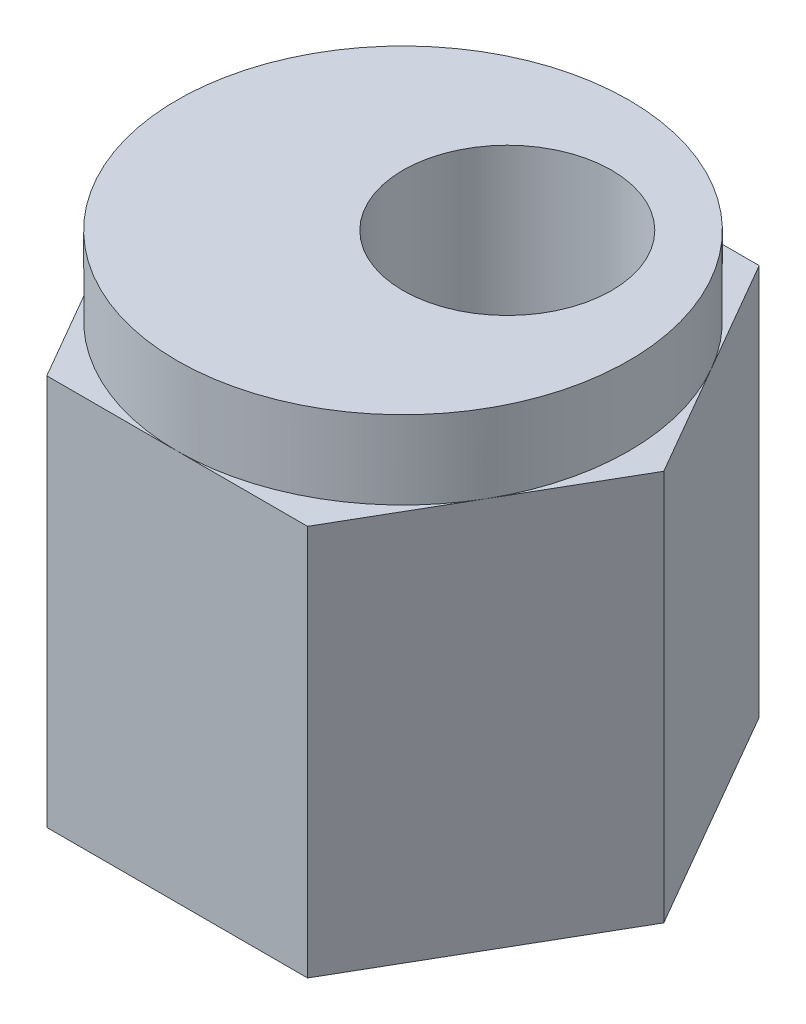
SolidWorks part; units mm, degrees
ref_plane "Front Plane" through (0, 0, 0) normal (0, 0, 1) x (1, 0, 0)
ref_plane "Top Plane" through (0, 0, 0) normal (0, 1, 0) x (1, 0, 0)
ref_plane "Right Plane" through (0, 0, 0) normal (1, 0, 0) x (0, 0, -1)
sketch "Sketch1" plane through (0, 0, 0) normal (0, 1, 0) x (1, 0, 0)
  line L1 (10, 0) -> (5, 8.6603)
  line L2 (5, 8.6603) -> (-5, 8.6603)
  line L3 (-5, 8.6603) -> (-10, 0)
  line L4 (-10, 0) -> (-5, -8.6603)
  line L5 (-5, -8.6603) -> (5, -8.6603)
  line L6 (5, -8.6603) -> (10, 0)
  circle A0 centre (0, 0) radius 8.6603 construction
  circle A1 centre (2, 2) radius 4
  dimension "D2" = 8
  dimension "D1" = 10
  dimension "D3" = 2
  dimension "D4" = 2
extrude "Boss-Extrude1" add sketch "Sketch1" along normal blind 18
sketch "Sketch3" plane through (0, 18, 0) normal (0, 1, 0) x (1, 0, 0)
  circle A0 centre (0, 0) radius 8.6603
  circle A1 centre (0, 0) radius 13.9766
extrude "Cut-Extrude1" cut sketch "Sketch3" against normal blind 3
